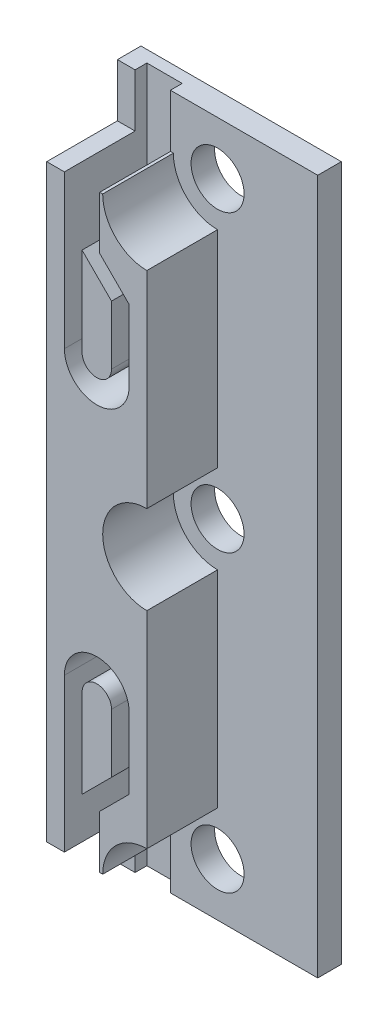
SolidWorks part; units mm, degrees
ref_plane "Plan de face" through (0, 0, 0) normal (0, 0, 1) x (1, 0, 0)
ref_plane "Plan de dessus" through (0, 0, 0) normal (0, 1, 0) x (1, 0, 0)
ref_plane "Plan de droite" through (0, 0, 0) normal (1, 0, 0) x (0, 0, -1)
sketch "Esquisse1" plane through (0, 0, 0) normal (0, 0, 1) x (1, 0, 0)
  line L1 (0, 0) -> (17, 0)
  line L2 (0, 0) -> (0, -59)
  line L3 (0, -59) -> (17, -59)
  line L4 (17, 0) -> (17, -59)
  dimension "D1" = 17
  dimension "D2" = 59
extrude "Boss.-Extru.1" add sketch "Esquisse1" along normal blind 2
sketch "Esquisse2" plane through (0, 0, 2) normal (0, 0, 1) x (1, 0, 0)
  line L0 (0, -59) -> (17, -59) construction
  line L1 (0, 0) -> (8.5, 0)
  line L2 (0, 0) -> (0, -59)
  line L3 (0, -59) -> (8.5, -59)
  line L4 (8.5, 0) -> (8.5, -59)
  line L5 (8.5, -54.5) -> (0, -54.5)
  line L6 (8.5, -4.5) -> (0, -4.5)
  dimension "D1" = 4.5
  dimension "D2" = 4.5
extrude "Boss.-Extru.2" add sketch "Esquisse2" along normal blind 6 contours L4 L6 L2 L5
sketch "Esquisse4" plane through (0, 0, 8) normal (0, 0, 1) x (1, 0, 0)
  line L0 (8.5, -4.5) -> (8.5, -54.5) construction
  circle A0 centre (8.5, -54.5) radius 2.25
  circle A1 centre (8.5, -29.5) radius 2.25
  circle A2 centre (8.5, -4.5) radius 2.25
  dimension "D1" = 4.5
  dimension "D2" = 4.5
  dimension "D3" = 4.5
extrude "Enlèv. mat.-Extru.6" cut sketch "Esquisse4" against normal blind 27
sketch "Esquisse3" plane through (0, 0, 8) normal (0, 0, 1) x (1, 0, 0)
  line L0 (3, -42) -> (5.5, -42)
  line L1 (0, -4.5) -> (0, -54.5) construction
  line L2 (1.5, -61.5) -> (1.5, -41.5)
  line L3 (1.5, -41.5) -> (3, -41.5)
  line L4 (3, -61.5) -> (3, -41.5)
  line L7 (3, -61.5) -> (3, -41.5)
  line L8 (3, -41.5) -> (4.5, -41.5)
  line L9 (4.5, -61.5) -> (4.5, -41.5)
  line L11 (4.5, -61.5) -> (4.5, -41.5)
  line L12 (4.5, -41.5) -> (7, -41.5)
  line L13 (7, -61.5) -> (7, -41.5)
  line L14 (5.5, -47) -> (3, -49.5)
  line L15 (8.5, -4.5) -> (8.5, -54.5) construction
  line L16 (4.25, -38.75) -> (4.25, -41.5)
  line L17 (5.5, -41.5) -> (7, -41.5)
  line L18 (5.5, -41.5) -> (5.5, -47)
  line L19 (1.5, -61.5) -> (3, -61.5)
  line L20 (7, -41.5) -> (7, -47.5)
  line L21 (7, -47.5) -> (4.5, -50)
  line L22 (3, -61.5) -> (4.5, -61.5)
  line L23 (4.5, -61.5) -> (7, -61.5)
  arc A0 (1.5, -41.5) -> (7, -41.5) centre (4.25, -41.5) cw
  arc A1 (3, -42) -> (5.5, -42) centre (4.25, -42) cw
  dimension "D5" = 1.5
  dimension "D8" = 1.5
  dimension "D9" = 45
  dimension "D7" = 0.5
  dimension "D2" = 1.5
  dimension "D3" = 1.5
  dimension "D4" = 1.5
  dimension "D6" = 1.25
  dimension "D10" = 1.5
  dimension "D11" = 20
  dimension "D12" = 13
  dimension "D13" = 45
  dimension "D14" = 2.5
extrude "Enlèv. mat.-Extru.7" cut sketch "Esquisse3" against normal blind 7
ref_plane "Plan1" through (0, -29.5, 0) normal (0, 1, 0) x (1, 0, 0)
mirror "Symétrie1" about plane through (0, -29.5, 0) normal (0, 1, 0) of "Enlèv. mat.-Extru.7"
sketch "Esquisse5" plane through (0, 0, 8) normal (0, 0, 1) x (1, 0, 0)
  circle A0 centre (8.5, -29.5) radius 3.75
  circle A1 centre (8.5, -4.5) radius 3.75
  circle A2 centre (8.5, -54.5) radius 3.75
  dimension "D1" = 7.5
  dimension "D2" = 7.5
  dimension "D3" = 7.5
extrude "Enlèv. mat.-Extru.8" cut sketch "Esquisse5" against normal blind 6
